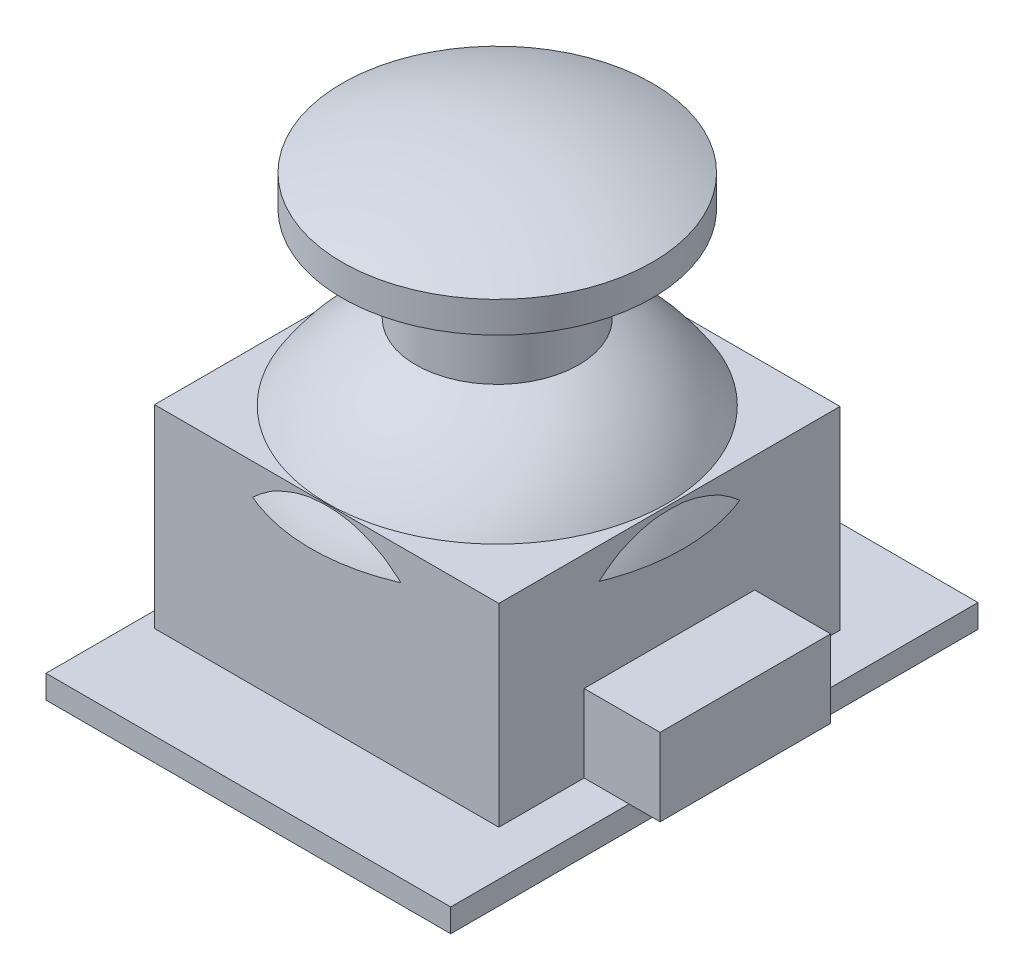
SolidWorks part; units mm, degrees
ref_plane "Front Plane" through (0, 0, 0) normal (0, 0, 1) x (1, 0, 0)
ref_plane "Top Plane" through (0, 0, 0) normal (0, 1, 0) x (1, 0, 0)
ref_plane "Right Plane" through (0, 0, 0) normal (1, 0, 0) x (0, 0, -1)
sketch "Sketch1" plane through (0, 0, 0) normal (0, 1, 0) x (1, 0, 0)
  line L1 (-13.05, 17) -> (13.05, 17)
  line L2 (-13.05, 17) -> (-13.05, -17)
  line L3 (-13.05, -17) -> (13.05, -17)
  line L4 (13.05, 17) -> (13.05, -17)
  line L5 (0, -17) -> (0, 17) construction
  line L6 (-13.05, 0) -> (13.05, 0) construction
  point P0 (0, 0)
  dimension "D1" = 34
  dimension "D2" = 26.1
extrude "Boss-Extrude1" add sketch "Sketch1" along normal blind 1.5
sketch "Sketch2" plane through (0, 1.5, 0) normal (0, 1, 0) x (1, 0, 0)
  line L1 (-12.05, 11) -> (10.15, 11)
  line L2 (-12.05, 11) -> (-12.05, -11)
  line L3 (-12.05, -11) -> (10.15, -11)
  line L4 (10.15, 11) -> (10.15, -11)
  line L10 (-12.05, -11) -> (10.15, 11) construction
  line L11 (-13.05, 17) -> (13.05, 17) construction
  line L12 (13.05, 17) -> (13.05, -17) construction
  line L13 (-13.05, 17) -> (-13.05, -17) construction
  line L14 (-13.05, 17) -> (-13.05, -17) construction
  point P0 (-0.95, 0)
  point P4 (-0.95, 0)
  point P5 (-8.3038, 13.5223)
  point P12 (10.15, 12.6326)
  point P13 (0, 0)
  dimension "D1" = 17
  dimension "D2" = 14
  dimension "D3" = 1
  dimension "D4" = 6
  dimension "D5" = 12.1
extrude "Boss-Extrude2" add sketch "Sketch2" along normal blind 12.5 separate body
sketch "Sketch3" plane through (0, 1.5, 0) normal (0, 1, 0) x (1, 0, 0)
  line L1 (10.15, 5.5) -> (15.05, 5.5)
  line L2 (10.15, 5.5) -> (10.15, -5.5)
  line L3 (10.15, -5.5) -> (15.05, -5.5)
  line L4 (15.05, 5.5) -> (15.05, -5.5)
  line L5 (10.15, 11) -> (10.15, -11) construction
  line L6 (13.05, -17) -> (13.05, 17) construction
  point P8 (10.15, 0)
  point P9 (10.15, 0)
  dimension "D1" = 11
  dimension "D2" = 2
extrude "Boss-Extrude3" add sketch "Sketch3" along normal blind 5
sketch "Sketch4" plane through (0, 14, 0) normal (0, 1, 0) x (1, 0, 0)
  circle A0 centre (0, 0) radius 2
  point P2 (2.7758, 2.029)
  point P3 (0, 0)
  point P5 (0, 0)
  dimension "D1" = 4
extrude "Boss-Extrude4" add sketch "Sketch4" along normal blind 7.5
sketch "Sketch5" plane through (0, 21.5, 0) normal (0, 1, 0) x (1, 0, 0)
  line L0 (-13.05, 0) -> (13.05, 0) construction
  line L1 (1.5, 1.3229) -> (2, 1.3229)
  line L2 (1.5, 1.3229) -> (1.5, -1.3229)
  line L3 (1.5, -1.3229) -> (2, -1.3229)
  line L4 (2, 1.3229) -> (2, -1.3229)
  line L5 (0, -17) -> (0, 17) construction
  circle A1 centre (0, 0) radius 2 construction
  point P4 (0.8096, -1.8288)
  point P7 (2, 1.9523)
  point P8 (0, 0)
  point P11 (2, 0)
  point P12 (0.9645, 1.7521)
  dimension "D1" = 1.5
extrude "Cut-Extrude1" cut sketch "Sketch5" against normal offset from surface (6.5 mm away) 1 up to face at (0, 14, 2)
mirror "Mirror1" about plane through (0, 0, 0) normal (1, 0, 0) of "Cut-Extrude1"
sketch "Sketch9" plane through (0, 0, 0) normal (0, 0, 1) x (1, 0, 0)
  line L0 (-0.95, 18.3441) -> (-0.95, 29.2)
  line L1 (-999.9174, 29.2) -> (49000.0826, 29.2) construction
  line L4 (-997.6311, 7) -> (49002.3689, 7) construction
  line L5 (14.355, 0) -> (-14.355, 0) construction
  line L6 (4.3, 25) -> (4.3, 18.8927)
  line L7 (4.3, 25) -> (9.05, 25)
  line L8 (9.05, 25) -> (9.05, 27)
  line L9 (-1021.7489, 12) -> (48978.2511, 12) construction
  line L10 (10.5064, 12) -> (11.05, 12)
  line L11 (4.3, 18.3441) -> (-0.95, 18.3441)
  line L13 (-0.95, -961.886) -> (-0.95, 49038.114) construction
  circle A0 centre (-0.95, 7) radius 13 construction
  arc A3 (4.3, 18.8927) -> (11.05, 12) centre (-0.95, 7) cw
  arc A4 (-0.95, 29.2) -> (9.05, 27) centre (-0.95, 5.3727) cw
  arc A5 (4.3, 18.3441) -> (10.5064, 12) centre (-0.95, 7) cw
  dimension "D1" = 26
  dimension "D9" = 0.5
  dimension "D2" = 7
  dimension "D3" = 5
  dimension "D4" = 5.25
  dimension "D5" = 2
  dimension "D6" = 13
  dimension "D7" = 17.2
  dimension "D8" = 10
revolve "Revolve1" add sketch "Sketch9" angle 360 about L13
